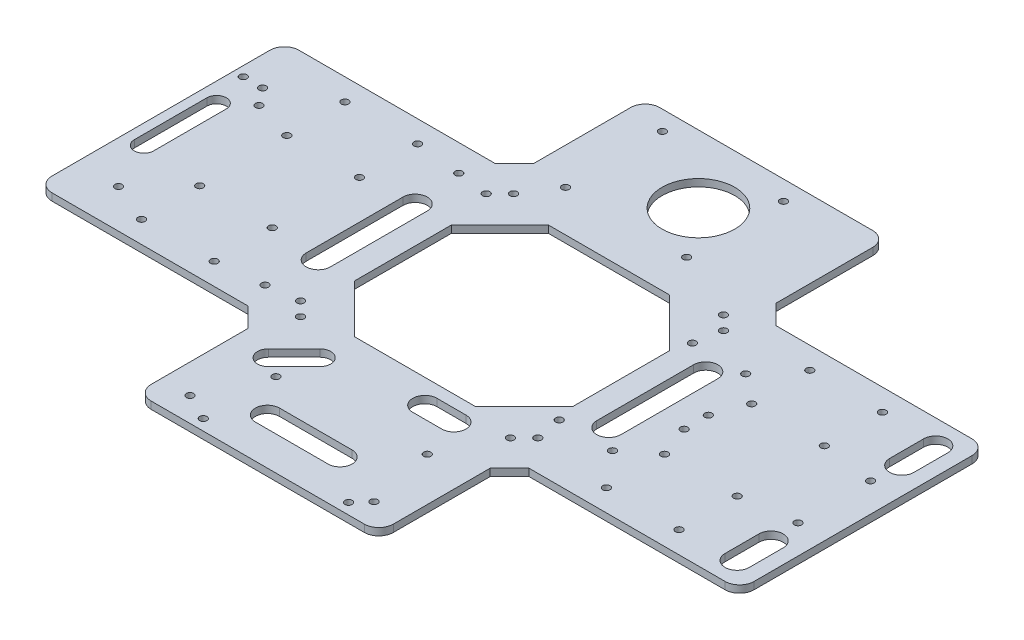
SolidWorks part; units mm, degrees
material "Thornel Mat VMA"
ref_plane "前视基准面" through (0, 0, 0) normal (0, 0, 1) x (1, 0, 0)
ref_plane "上视基准面" through (0, 0, 0) normal (0, 1, 0) x (1, 0, 0)
ref_plane "右视基准面" through (0, 0, 0) normal (1, 0, 0) x (0, 0, -1)
other "Configuration Table"
sketch "草图1" plane through (0, 0, 0) normal (0, 1, 0) x (1, 0, 0)
  line L0 (0, 0) -> (0, 105) construction
  line L1 (-145, -105) -> (145, -105)
  line L2 (-145, -105) -> (-145, 105)
  line L3 (-145, 105) -> (145, 105)
  line L4 (145, -105) -> (145, 105)
  line L5 (-145, -105) -> (145, 105) construction
  line L6 (-145, 105) -> (145, -105) construction
  line L7 (0, 0) -> (145, 0) construction
  line L8 (-50, 105) -> (-50, 51)
  line L9 (-50, 51) -> (-145, 51)
  line L10 (50, 51) -> (145, 51)
  line L11 (50, 105) -> (50, 51)
  line L12 (50, -51) -> (145, -51)
  line L13 (50, -105) -> (50, -51)
  line L14 (-50, -51) -> (-145, -51)
  line L15 (-50, -105) -> (-50, -51)
  point P0 (0, 0)
  dimension "D1" = 290
  dimension "D2" = 210
  dimension "D3" = 102
  dimension "D4" = 100
extrude "凸台-拉伸1" add sketch "草图1" along normal blind 3 contours L15 L1 L13 L12 L4 L10 L11 L3 L8 L9 L2 L14
sketch "草图2" plane through (0, 3, 0) normal (0, 1, 0) x (1, 0, 0)
  line L0 (0, 0) -> (145, 0) construction
  line L1 (145, -51) -> (145, 51) construction
  line L2 (0, 0) -> (0, 105) construction
  line L3 (-50, 105) -> (50, 105) construction
  line L4 (50, 51) -> (145, 51) construction
  circle A0 centre (111, 42) radius 1.5
  circle A1 centre (81, 42) radius 1.5
  circle A2 centre (81, 18) radius 1.5
  circle A3 centre (111, 18) radius 1.5
  circle A4 centre (111, -18) radius 1.5
  circle A5 centre (111, -42) radius 1.5
  circle A6 centre (81, -18) radius 1.5
  circle A7 centre (81, -42) radius 1.5
  circle A8 centre (-81, -42) radius 1.5
  circle A9 centre (-81, -18) radius 1.5
  circle A10 centre (-111, -42) radius 1.5
  circle A11 centre (-111, -18) radius 1.5
  circle A12 centre (-111, 18) radius 1.5
  circle A13 centre (-81, 18) radius 1.5
  circle A14 centre (-81, 42) radius 1.5
  circle A15 centre (-111, 42) radius 1.5
  dimension "D1" = 3
  dimension "D2" = 3
  dimension "D3" = 3
  dimension "D4" = 3
  dimension "D11" = 81
  dimension "D12" = 9
  dimension "D5" = 24
  dimension "D6" = 24
  dimension "D7" = 30
  dimension "D8" = 30
  dimension "D9" = 81
  dimension "D10" = 9
extrude "切除-拉伸1" cut sketch "草图2" against normal blind 3
sketch "草图3" plane through (0, 3, 0) normal (0, 1, 0) x (1, 0, 0)
  line L0 (-9.89, 0) -> (-9.89, 110.5115) construction
  line L1 (-9.89, 0) -> (145, 0) construction
  line L2 (145, -51) -> (145, 51) construction
  line L3 (-86.4083, 77) -> (66.6283, 77) construction
  line L4 (0, 0) -> (0, 108.4938) construction
  line L6 (-37, -104.5) -> (43, -104.5) construction
  line L7 (0, 0) -> (0, -114.288) construction
  line L8 (-37, -104.5) -> (-37, -49.5) construction
  line L9 (-37, -49.5) -> (43, -49.5) construction
  line L10 (43, -104.5) -> (43, -49.5) construction
  line L11 (-37, -104.5) -> (43, -49.5) construction
  line L12 (-37, -49.5) -> (43, -104.5) construction
  circle A5 centre (0, 77) radius 15
  circle A33 centre (15.11, 97) radius 1.5
  circle A34 centre (15.11, 57) radius 1.5
  circle A35 centre (-34.89, 57) radius 1.5
  circle A36 centre (-34.89, 97) radius 1.5
  circle A37 centre (-27, -70.5) radius 1.5
  circle A38 centre (32, -67) radius 1.5
  circle A39 centre (-27, -100.5) radius 1.5
  circle A40 centre (33, -100.5) radius 1.5
  point P4 (3, -77)
  point P13 (-9.89, 77)
  dimension "D2" = 77
  dimension "D6" = 30
  dimension "D7" = 77
  dimension "D11" = 3
  dimension "D12" = 20
  dimension "D13" = 3
  dimension "D15" = 17.5
  dimension "D17" = 10
  dimension "D18" = 51
  dimension "D20" = 70
  dimension "D3" = 80
  dimension "D8" = 3
  dimension "D10" = 3
  dimension "D14" = 3
  dimension "D21" = 70
  dimension "D22" = 51
  dimension "D4" = 55
  dimension "D5" = 9.89
  dimension "D9" = 25
  dimension "D16" = 11
  dimension "D19" = 21
  dimension "D23" = 3
extrude "切除-拉伸2" cut sketch "草图3" against normal blind 10
sketch "草图4" plane through (0, 3, 0) normal (0, 1, 0) x (1, 0, 0)
  line L1 (-45, -40) -> (45, -40)
  line L2 (-45, -40) -> (-45, 40)
  line L3 (-45, 40) -> (45, 40)
  line L4 (45, -40) -> (45, 40)
  line L5 (-45, -40) -> (45, 40) construction
  line L6 (-45, 40) -> (45, -40) construction
  point P0 (0, 0)
  dimension "D1" = 90
  dimension "D2" = 80
extrude "切除-拉伸3" cut sketch "草图4" against normal blind 3
fillet "圆角3" radius 6 8 edges at (-50, 1.5, -105) (50, 1.5, -105) (145, 1.5, -51) (145, 1.5, 51) (-50, 1.5, 105) (50, 1.5, 105) (-145, 1.5, 51) (-145, 1.5, -51)
chamfer "倒角1" distance 8 angle 45 4 edges at (50, 1.5, 51) (-50, 1.5, 51) (50, 1.5, -51) (-50, 1.5, -51)
sketch "草图7" plane through (0, 3, 0) normal (0, 1, 0) x (1, 0, 0)
  line L0 (0, 0) -> (0, 142.9478) construction
  line L1 (0, 0) -> (-184.5222, 0) construction
  line L2 (-137, -15) -> (-137, 15) construction
  line L5 (-60, -20) -> (-60, 20) construction
  line L6 (-65, -20) -> (-65, 20)
  line L7 (-55, -20) -> (-55, 20)
  line L8 (0, 0) -> (165.4514, 0) construction
  line L14 (-110, 0) -> (-110, 75.2826) construction
  line L15 (134, 27) -> (134, 41) construction
  line L21 (60, -20) -> (60, 20) construction
  line L22 (65, -20) -> (65, 20)
  line L23 (55, -20) -> (55, 20)
  line L33 (-141, -15) -> (-141, 15)
  line L34 (-133, -15) -> (-133, 15)
  line L35 (63, 0) -> (63, 55.2292) construction
  line L36 (0, -15) -> (172.3256, -15) construction
  line L38 (129, 27) -> (129, 41)
  line L39 (139, 27) -> (139, 41)
  line L40 (134, -27) -> (134, -41) construction
  line L41 (129, -27) -> (129, -41)
  line L42 (139, -27) -> (139, -41)
  arc A2 (-65, -20) -> (-55, -20) centre (-60, -20) ccw
  arc A3 (-55, 20) -> (-65, 20) centre (-60, 20) ccw
  arc A18 (65, -20) -> (55, -20) centre (60, -20) cw
  arc A19 (55, 20) -> (65, 20) centre (60, 20) cw
  arc A34 (-141, -15) -> (-133, -15) centre (-137, -15) ccw
  arc A35 (-133, 15) -> (-141, 15) centre (-137, 15) ccw
  circle A47 centre (47, 27.5) radius 1.5
  circle A49 centre (47, -27.5) radius 1.5
  circle A50 centre (69, 27.5) radius 1.5
  circle A51 centre (69, -27.5) radius 1.5
  arc A56 (129, 27) -> (139, 27) centre (134, 27) ccw
  arc A57 (139, 41) -> (129, 41) centre (134, 41) ccw
  arc A58 (129, -27) -> (139, -27) centre (134, -27) cw
  arc A59 (139, -41) -> (129, -41) centre (134, -41) cw
  point P6 (-137, 0)
  point P13 (-60, 0)
  point P21 (134, 34)
  point P27 (60, 0)
  point P37 (134, -34)
  dimension "D2" = 30
  dimension "D5" = 5
  dimension "D8" = 5
  dimension "D10" = 34
  dimension "D9" = 134
  dimension "D3" = 4
  dimension "D22" = 3
  dimension "D23" = 15
  dimension "D25" = 55
  dimension "D26" = 55
  dimension "D27" = 3
  dimension "D29" = 6
  dimension "D1" = 14
  dimension "D4" = 40
  dimension "D6" = 60
  dimension "D7" = 110
  dimension "D20" = 133
  dimension "D24" = 63
  dimension "D28" = 16
extrude "切除-拉伸6" cut sketch "草图7" against normal blind 10
chamfer "倒角2" distance 20 angle 45 4 edges at (45, 1.5, 40) (-45, 1.5, 40) (45, 1.5, -40) (-45, 1.5, -40)
sketch "草图8" plane through (0, 3, 0) normal (0, 1, 0) x (1, 0, 0)
  line L0 (0, 0) -> (0, 168.9929) construction
  line L1 (0, 0) -> (-169.1558, 0) construction
  line L2 (-103, 0) -> (-103, 65.828) construction
  line L3 (-103, -6) -> (-155.6162, -6) construction
  line L4 (0, 0) -> (-184.1789, 0) construction
  line L5 (0, 0) -> (0, 73.477) construction
  line L6 (-58, 51) -> (-139, 51) construction
  line L7 (-145, -45) -> (-145, 45) construction
  circle A12 centre (-127.5, 23) radius 1.5
  circle A14 centre (-127.5, -35) radius 1.5
  circle A15 centre (-141, 30) radius 1.5
  circle A16 centre (-133, 30) radius 1.5
  dimension "D1" = 3
  dimension "D2" = 24.5
  dimension "D3" = 58
  dimension "D4" = 103
  dimension "D5" = 6
  dimension "D6" = 0
  dimension "D7" = 3
  dimension "D8" = 3
  dimension "D9" = 8
  dimension "D11" = 30
  dimension "D12" = 38
  dimension "D10" = 21
extrude "切除-拉伸7" cut sketch "草图8" against normal blind 10
sketch "草图9" plane through (0, 3, 0) normal (0, 1, 0) x (1, 0, 0)
  line L0 (0, 0) -> (0, 165.3902) construction
  line L1 (0, 0) -> (179.4814, 0) construction
  line L2 (43.3431, 44) -> (49, 38.3431) construction
  line L3 (-55, -50) -> (55, -50) construction
  line L4 (-55, -50) -> (-55, 50) construction
  line L5 (-55, 50) -> (55, 50) construction
  line L6 (55, -50) -> (55, 50) construction
  line L7 (-55, -50) -> (55, 50) construction
  line L8 (-55, 50) -> (55, -50) construction
  circle A0 centre (43.3431, 44) radius 1.5
  circle A1 centre (49, 38.3431) radius 1.5
  circle A2 centre (49, -38.3431) radius 1.5
  circle A3 centre (43.3431, -44) radius 1.5
  circle A4 centre (-43.3431, -44) radius 1.5
  circle A5 centre (-49, -38.3431) radius 1.5
  circle A6 centre (-49, 38.3431) radius 1.5
  circle A7 centre (-43.3431, 44) radius 1.5
  circle A8 centre (-38, -95) radius 1.5
  circle A9 centre (38, -95) radius 1.5
  circle A10 centre (-62, 40) radius 1.5
  circle A11 centre (-62, -40) radius 1.5
  dimension "D3" = 3
  dimension "D4" = 3
  dimension "D6" = 8
  dimension "D9" = 3
  dimension "D11" = 95
  dimension "D12" = 3
  dimension "D13" = 62
  dimension "D14" = 80
  dimension "D1" = 110
  dimension "D2" = 100
  dimension "D5" = 45
  dimension "D7" = 6
  dimension "D8" = 6
  dimension "D10" = 38
extrude "切除-拉伸8" cut sketch "草图9" against normal blind 10
sketch "草图10" plane through (0, 3, 0) normal (0, 1, 0) x (1, 0, 0)
  line L0 (0, 0) -> (173.0266, 0) construction
  line L1 (0, 0) -> (0, 114.2255) construction
  circle A0 centre (76.1, 5) radius 1.5
  circle A1 centre (133.1, 15) radius 1.5
  circle A2 centre (133.1, -15) radius 1.5
  circle A3 centre (76.1, -5) radius 1.5
  dimension "D1" = 3
  dimension "D2" = 3
  dimension "D3" = 10
  dimension "D4" = 57
  dimension "D5" = 30
  dimension "D6" = 76.1
extrude "切除-拉伸9" cut sketch "草图10" against normal blind 10
sketch "草图11" plane through (0, 3, 0) normal (0, 1, 0) x (1, 0, 0)
  line L0 (0, 0) -> (183.5565, 0) construction
  line L1 (0, 0) -> (0, -155.5612) construction
  line L2 (-24.6967, -54.6967) -> (-35.3033, -65.3033) construction
  line L3 (-21.5147, -57.8787) -> (-32.1213, -68.4853)
  line L4 (-27.8787, -51.5147) -> (-38.4853, -62.1213)
  line L5 (14, -50) -> (26, -50) construction
  line L6 (14, -45) -> (26, -45)
  line L7 (14, -55) -> (26, -55)
  line L8 (-15, -86) -> (15, -86) construction
  line L9 (-15, -81) -> (15, -81)
  line L10 (-15, -91) -> (15, -91)
  arc A0 (-21.5147, -57.8787) -> (-27.8787, -51.5147) centre (-24.6967, -54.6967) ccw
  arc A1 (-38.4853, -62.1213) -> (-32.1213, -68.4853) centre (-35.3033, -65.3033) ccw
  arc A2 (14, -45) -> (14, -55) centre (14, -50) ccw
  arc A3 (26, -55) -> (26, -45) centre (26, -50) ccw
  arc A4 (-15, -81) -> (-15, -91) centre (-15, -86) ccw
  arc A5 (15, -91) -> (15, -81) centre (15, -86) ccw
  point P6 (-30, -60)
  point P13 (20, -50)
  point P20 (0, -86)
  dimension "D2" = 4.5
  dimension "D7" = 5
  dimension "D11" = 5
  dimension "D1" = 15
  dimension "D3" = 45
  dimension "D4" = 60
  dimension "D5" = 30
  dimension "D6" = 12
  dimension "D8" = 20
  dimension "D9" = 50
  dimension "D10" = 30
  dimension "D12" = 86
extrude "切除-拉伸10" cut sketch "草图11" against normal blind 10
